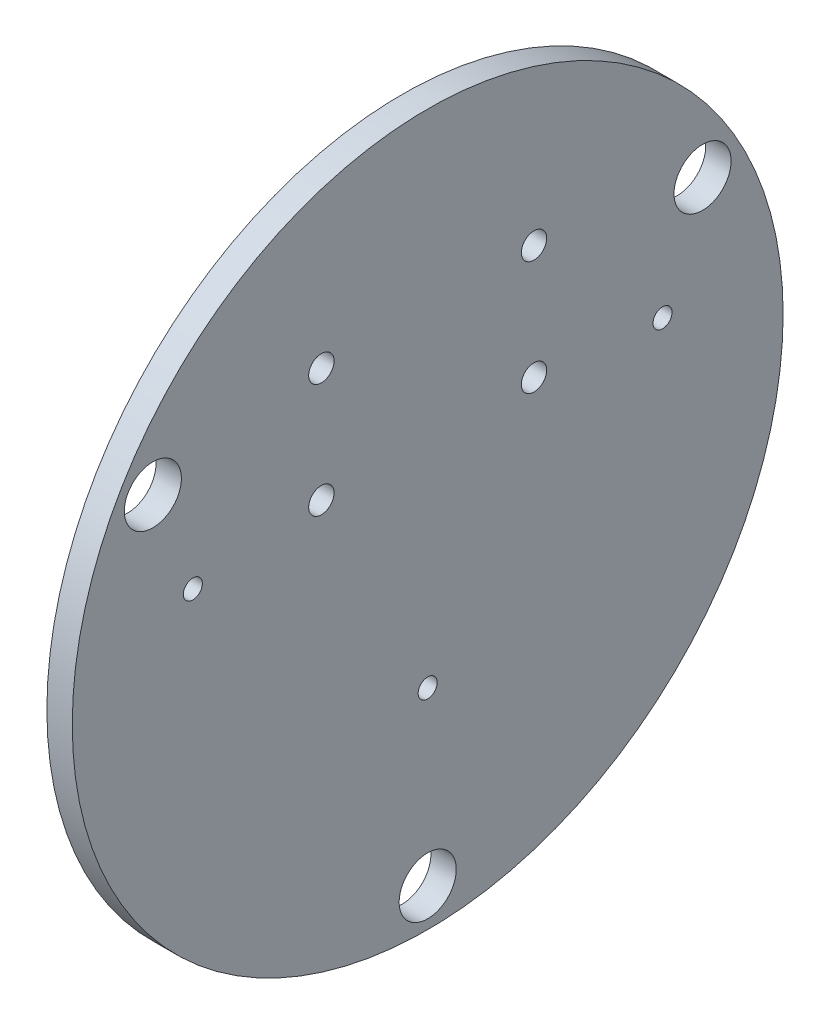
SolidWorks part; units mm, degrees
ref_plane "Ebene vorne" through (0, 0, 0) normal (0, 0, 1) x (1, 0, 0)
ref_plane "Ebene oben" through (0, 0, 0) normal (0, 1, 0) x (1, 0, 0)
ref_plane "Ebene rechts" through (0, 0, 0) normal (1, 0, 0) x (0, 0, -1)
sketch "Sketch1" plane through (0, 0, 0) normal (1, 0, 0) x (0, 0, -1)
  circle A0 centre (0, 0) radius 56
  dimension "D1" = 112
extrude "Boss-Extrude1" add sketch "Sketch1" along normal blind 4
sketch "Sketch2" plane through (0, 0, 0) normal (-1, 0, 0) x (0, 0, 1)
  line L0 (0, 0) -> (0, -56) construction
  circle A0 centre (-43.3013, 25) radius 4.5
  circle A1 centre (43.3013, 25) radius 4.5
  circle A2 centre (0, -50) radius 4.5
  circle A3 centre (0, 0) radius 56 construction
  point P9 (0, 0)
  dimension "D1" = 9
  dimension "D2" = 50
  dimension "D3" = 3
extrude "Cut-Extrude1" cut sketch "Sketch2" against normal through all
sketch "Sketch4" plane through (4, 0, 0) normal (1, 0, 0) x (0, 0, -1)
  line L0 (0, 56) -> (0, -40.0081) construction
  line L1 (16.75, 28.9955) -> (-48.2229, 28.9955) construction
  circle A0 centre (-16.75, 28.9955) radius 2
  circle A1 centre (16.75, 28.9955) radius 2
  circle A2 centre (16.75, 11) radius 2
  circle A3 centre (-16.75, 11) radius 2
  circle A4 centre (-37, 9) radius 1.5
  circle A5 centre (0, -23) radius 1.5
  circle A6 centre (37, 9) radius 1.5
  circle A7 centre (0, 0) radius 56 construction
  circle A8 centre (0, -50) radius 4.5 construction
  dimension "D1" = 4
  dimension "D2" = 3
  dimension "D5" = 33.5
  dimension "D7" = 2
  dimension "D3" = 32
  dimension "D4" = 17.9955
  dimension "D6" = 32
  dimension "D8" = 27
extrude "Cut-Extrude3" cut sketch "Sketch4" against normal through all
